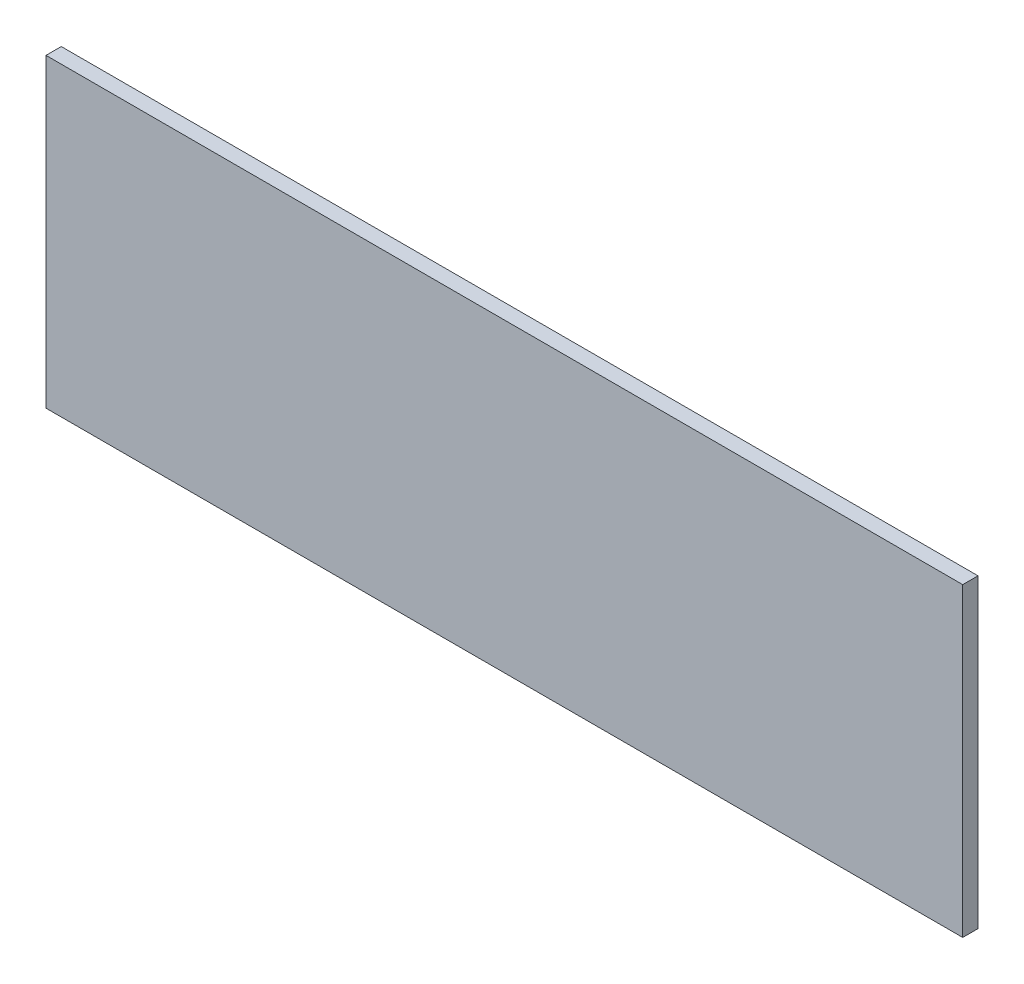
SolidWorks part; units mm, degrees
ref_plane "前视基准面" through (0, 0, 0) normal (0, 0, 1) x (1, 0, 0)
ref_plane "上视基准面" through (0, 0, 0) normal (0, 1, 0) x (1, 0, 0)
ref_plane "右视基准面" through (0, 0, 0) normal (1, 0, 0) x (0, 0, -1)
sketch "草图1" plane through (0, 0, 0) normal (0, 0, 1) x (1, 0, 0)
  line L1 (-6000, 2000) -> (6000, 2000)
  line L2 (-6000, 2000) -> (-6000, -2000)
  line L3 (-6000, -2000) -> (6000, -2000)
  line L4 (6000, 2000) -> (6000, -2000)
  line L5 (0, -2000) -> (0, 2000) construction
  line L6 (-6000, 0) -> (6000, 0) construction
  point P0 (0, 0)
  dimension "D1" = 12000
  dimension "D2" = 4000
extrude "凸台-拉伸1" add sketch "草图1" along normal blind 200
